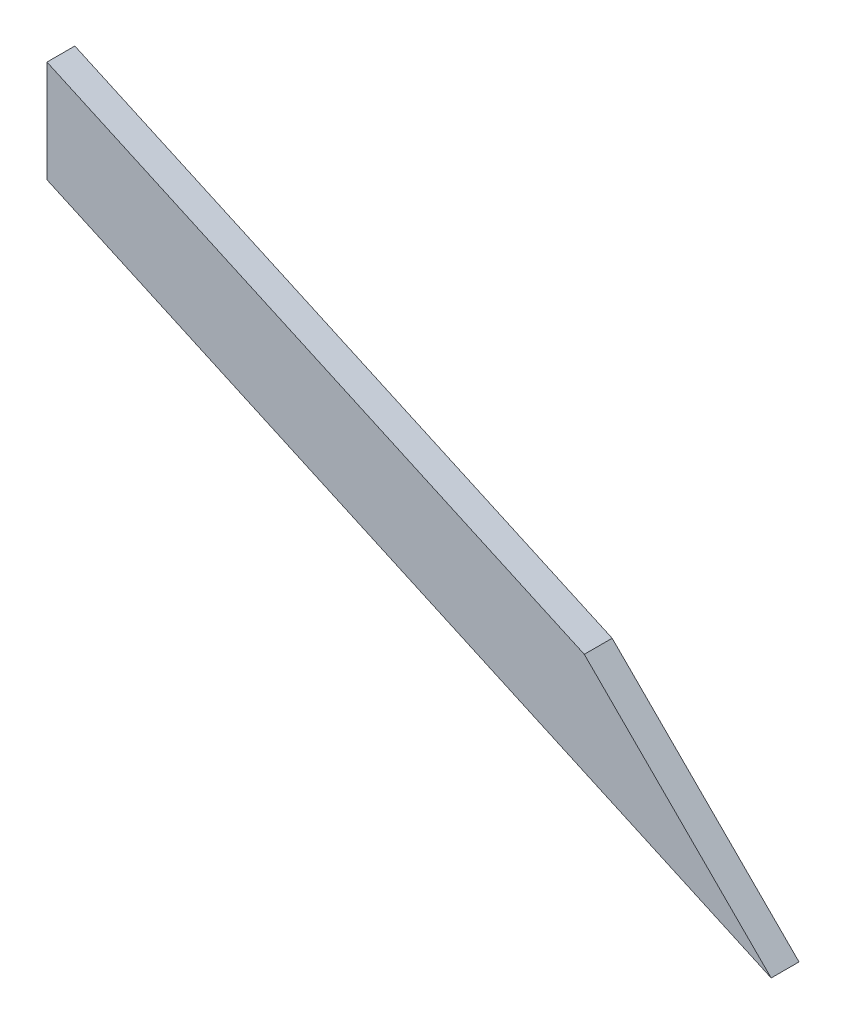
SolidWorks part; units mm, degrees
material "Pine"
ref_plane "Front Plane" through (0, 0, 0) normal (0, 0, 1) x (1, 0, 0)
ref_plane "Top Plane" through (0, 0, 0) normal (0, 1, 0) x (1, 0, 0)
ref_plane "Right Plane" through (0, 0, 0) normal (1, 0, 0) x (0, 0, -1)
sketch "Sketch5" plane through (0, 0, 0) normal (0, 0, 1) x (1, 0, 0)
  line L0 (-737.1845, 1692.941) -> (-737.1845, 1762.6932)
  line L1 (-737.1845, 1692.941) -> (-241.631, 1467.6894)
  line L2 (-241.631, 1467.6894) -> (-369.5099, 1595.5683)
  line L3 (-737.1845, 1762.6932) -> (-369.5099, 1595.5683)
extrude "Boss-Extrude1" add sketch "Sketch5" along normal blind 19.05
